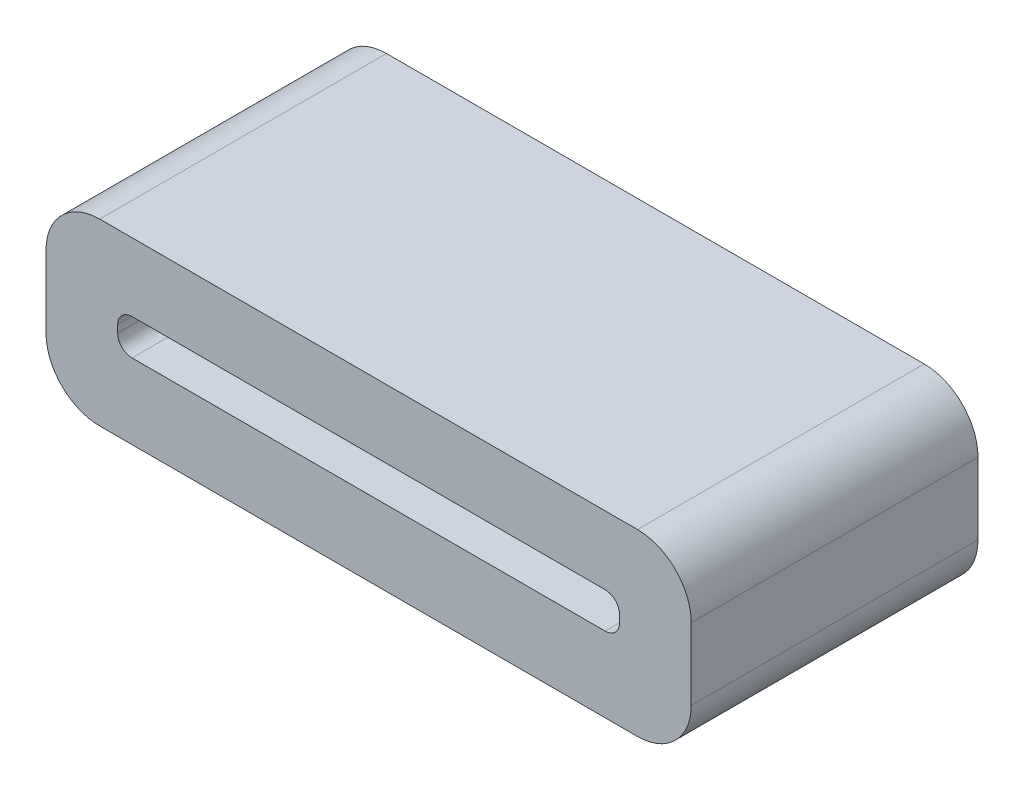
SolidWorks part; units mm, degrees
ref_plane "Face" through (0, 0, 0) normal (0, 0, 1) x (1, 0, 0)
ref_plane "Dessus" through (0, 0, 0) normal (0, 1, 0) x (1, 0, 0)
ref_plane "Droite" through (0, 0, 0) normal (1, 0, 0) x (0, 0, -1)
sketch "Esquisse1" plane through (0, 0, 0) normal (0, 0, 1) x (1, 0, 0)
  line L1 (1.5, 0) -> (16.5, 0)
  line L2 (0, 1.5) -> (0, 3.5)
  line L3 (1.5, 5) -> (16.5, 5)
  line L4 (18, 1.5) -> (18, 3.5)
  arc A0 (16.5, 5) -> (18, 3.5) centre (16.5, 3.5) cw
  arc A1 (16.5, 0) -> (18, 1.5) centre (16.5, 1.5) ccw
  arc A2 (1.5, 0) -> (0, 1.5) centre (1.5, 1.5) cw
  arc A3 (0, 3.5) -> (1.5, 5) centre (1.5, 3.5) cw
  point P7 (18, 5)
  point P10 (18, 0)
  point P13 (0, 0)
  point P16 (0, 5)
  dimension "D3" = 1.5
  dimension "D1" = 18
  dimension "D2" = 5
extrude "Extrusion1" add sketch "Esquisse1" along normal blind 8
sketch "Esquisse2" plane through (0, 0, 8) normal (0, 0, 1) x (1, 0, 0)
  line L0 (0.1118, 2.5954) -> (19.4566, 2.5954) construction
  line L1 (9, 5) -> (9, 0) construction
  line L2 (2.4, 3.0954) -> (15.6, 3.0954)
  line L3 (2, 2.6954) -> (2, 2.4954)
  line L4 (2.4, 2.0954) -> (15.6, 2.0954)
  line L5 (16, 2.6954) -> (16, 2.4954)
  line L6 (16.5, 5) -> (1.5, 5) construction
  line L7 (1.5, 0) -> (16.5, 0) construction
  arc A0 (2.4, 3.0954) -> (2, 2.6954) centre (2.4, 2.6954) ccw
  arc A1 (2, 2.4954) -> (2.4, 2.0954) centre (2.4, 2.4954) ccw
  arc A2 (15.6, 2.0954) -> (16, 2.4954) centre (15.6, 2.4954) ccw
  arc A3 (15.6, 3.0954) -> (16, 2.6954) centre (15.6, 2.6954) cw
  dimension "D5" = 0.4
  dimension "D1" = 0.5
  dimension "D2" = 0.5
  dimension "D3" = 7
  dimension "D4" = 7
extrude "Enlèv. mat.-Extru.1" cut sketch "Esquisse2" against normal blind 8
